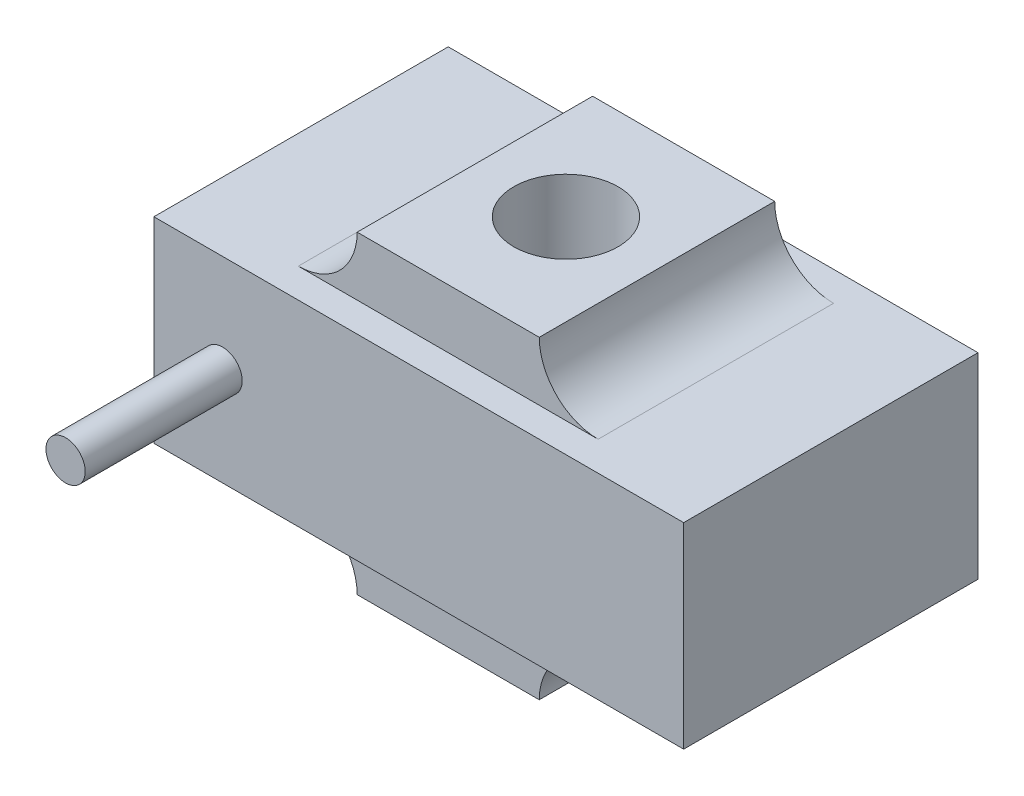
SolidWorks part; units mm, degrees
ref_plane "Front" through (0, 0, 0) normal (0, 0, 1) x (1, 0, 0)
ref_plane "Top" through (0, 0, 0) normal (0, 1, 0) x (1, 0, 0)
ref_plane "Right" through (0, 0, 0) normal (1, 0, 0) x (0, 0, -1)
sketch "Sketch1" plane through (0, 0, 0) normal (0, 0, 1) x (1, 0, 0)
  line L0 (-21.4312, 7.9375) -> (21.4312, -7.9375) construction
  line L1 (-21.4312, 7.9375) -> (21.4312, 7.9375)
  line L2 (-21.4312, 7.9375) -> (-21.4312, -7.9375)
  line L3 (-21.4312, -7.9375) -> (21.4312, -7.9375)
  line L4 (21.4312, 7.9375) -> (21.4312, -7.9375)
  dimension "D1" = 15.875
  dimension "D2" = 42.8625
extrude "Extrude1" add sketch "Sketch1" along normal mid plane 23.8125
sketch "Sketch2" plane through (0, 0, 0) normal (0, 0, 1) x (1, 0, 0)
  line L0 (-7.366, 12.7) -> (7.366, 12.7)
  line L1 (21.4312, 7.9375) -> (-21.4312, 7.9375) construction
  line L2 (0, 0) -> (23.3703, 0) construction
  line L3 (-7.366, -12.7) -> (7.366, -12.7)
  line L8 (-21.4312, 7.9375) -> (-21.4312, -7.9375)
  line L9 (-21.4312, -7.9375) -> (21.4312, -7.9375)
  line L10 (21.4312, -7.9375) -> (21.4312, 7.9375)
  line L11 (21.4312, 7.9375) -> (-21.4312, 7.9375)
  line L13 (-12.1285, -7.9375) -> (12.1285, -7.9375)
  line L15 (12.1285, 7.9375) -> (-12.1285, 7.9375)
  arc A0 (7.366, 12.7) -> (12.1285, 7.9375) centre (12.1285, 12.7) ccw
  arc A1 (-7.366, 12.7) -> (-12.1285, 7.9375) centre (-12.1285, 12.7) cw
  arc A2 (-7.366, -12.7) -> (-12.1285, -7.9375) centre (-12.1285, -12.7) ccw
  arc A3 (7.366, -12.7) -> (12.1285, -7.9375) centre (12.1285, -12.7) cw
  point P8 (0, 12.7)
  dimension "D1" = 14.732
  dimension "D2" = 25.4
  dimension "D3" = 0
extrude "Extrude2" add sketch "Sketch2" along normal mid plane 19.05
hole_wizard "3/8-24 Tapped Hole1" positions "Sketch4" profile "Sketch3" tap size "3/8-24" standard "Ansi Inch"
sketch "Sketch4" plane through (0, 12.7, 0) normal (0, 1, 0) x (-1, 0, 0)
  point P0 (0, 0)
sketch "Sketch3" plane through (0, 12.7, 0) normal (1, 0, 0) x (0, 0, 1)
  line L0 (0, 0) -> (0, 12.0585)
  line L1 (0, 12.0585) -> (4.2164, 9.525)
  line L2 (4.2164, 9.525) -> (4.2164, 0)
  line L5 (4.2164, 0) -> (0, 0)
  line L10 (0, 12.0585) -> (-4.2164, 9.525) construction
  line L11 (0, -6.35) -> (0, 107.95) construction
  dimension "Tap Drill Dia." = 8.4328
  dimension "Tap Drill Depth" = 9.525
  dimension "Drill Angle" = 118
cosmetic thread "Hole Thread1" parameters "D1"=9.525, "D2"=9.525
cosmetic thread "Hole Thread2" parameters "D1"=9.525, "D2"=9.525
hole_wizard "3/8-24 Tapped Hole2" positions "Sketch6" profile "Sketch5" tap size "3/8-24" standard "Ansi Inch"
sketch "Sketch6" plane through (0, -12.7, 0) normal (0, -1, 0) x (1, 0, 0)
  point P0 (0, 0)
sketch "Sketch5" plane through (0, -12.7, 0) normal (1, 0, 0) x (0, 0, -1)
  line L0 (0, 0) -> (0, 12.0585)
  line L1 (0, 12.0585) -> (4.2164, 9.525)
  line L2 (4.2164, 9.525) -> (4.2164, 0)
  line L5 (4.2164, 0) -> (0, 0)
  line L10 (0, 12.0585) -> (-4.2164, 9.525) construction
  line L11 (0, -6.35) -> (0, 107.95) construction
  dimension "Tap Drill Dia." = 8.4328
  dimension "Tap Drill Depth" = 9.525
  dimension "Drill Angle" = 118
cosmetic thread "Hole Thread3" parameters "D1"=9.525, "D2"=9.525
sketch "Sketch7" plane through (0, 0, 11.9062) normal (0, 0, 1) x (1, 0, 0)
  circle A0 centre (-15.875, 0) radius 1.5875
  dimension "D1" = 15.875
  dimension "D2" = 3.175
extrude "Extrude3" add sketch "Sketch7" along normal blind 12.7
